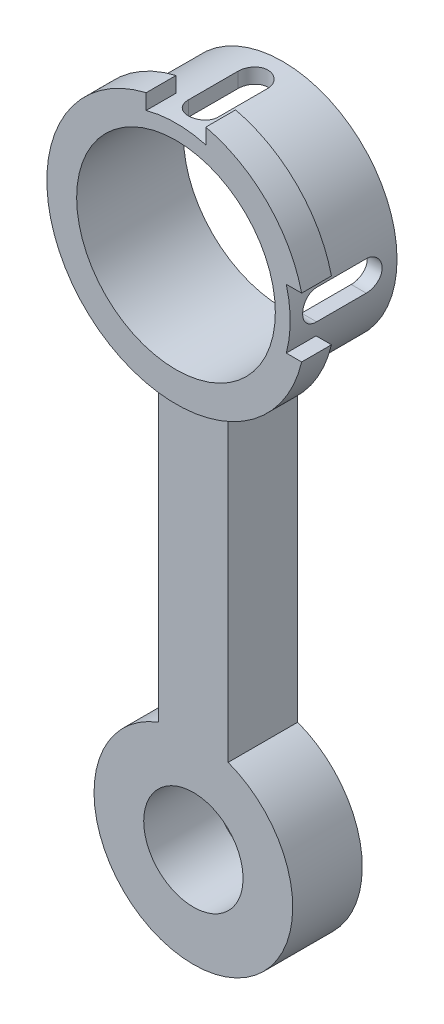
SolidWorks part; units mm, degrees
ref_plane "Alzado" through (0, 0, 0) normal (0, 0, 1) x (1, 0, 0)
ref_plane "Planta" through (0, 0, 0) normal (0, 1, 0) x (1, 0, 0)
ref_plane "Vista lateral" through (0, 0, 0) normal (1, 0, 0) x (0, 0, -1)
sketch "Croquis1" plane through (0, 0, 0) normal (0, 0, 1) x (1, 0, 0)
  circle A0 centre (0, 0) radius 10
  dimension "D1" = 20
extrude "Saliente-Extruir1" add sketch "Croquis1" along normal blind 3
sketch "Croquis2" plane through (0, 0, 3) normal (0, 0, 1) x (1, 0, 0)
  circle A0 centre (0, 0) radius 2.5
  circle A1 centre (0, 0) radius 4
  circle A2 centre (0, 0) radius 11.5
  circle A3 centre (0, 0) radius 10
  circle M1 centre (0, 0) radius 10
  dimension "D1" = 5
  dimension "D2" = 8
  dimension "D3" = 23
extrude "Saliente-Extruir3" add sketch "Croquis2" along normal blind 8 separate body contours A2 M1
sketch "Croquis3" plane through (0, 0, 3) normal (0, 0, -1) x (-1, 0, 0)
  circle A0 centre (0, 0) radius 11.5
  circle A1 centre (0, 0) radius 10
extrude "Saliente-Extruir4" add sketch "Croquis3" along normal up to surface (3 mm away) up to face at (10, 0, 0)
ref_plane "Plano1" through (0, 11.5, 0) normal (0, 1, 0) x (1, 0, 0)
sketch "Croquis4" plane through (0, 11.5, 0) normal (0, 1, 0) x (1, 0, 0)
  line L0 (0, -9.5) -> (0, -11) construction
  line L2 (0, -8) -> (0, -3) construction
  line L3 (-1.5, -8) -> (-1.5, -3)
  line L4 (1.5, -8) -> (1.5, -3)
  line L5 (-11.5, -11) -> (11.5, -11) construction
  line L6 (0, -1.5) -> (0, 0) construction
  arc A1 (-1.5, -8) -> (1.5, -8) centre (0, -8) ccw
  arc A2 (1.5, -3) -> (-1.5, -3) centre (0, -3) ccw
  point P0 (0, -5.5)
  dimension "D2" = 1.5
  dimension "D1" = 1.5
  dimension "D3" = 1.5
extrude "Cortar-Extruir1" cut sketch "Croquis4" against normal blind 8
sketch "Croquis7" plane through (0, 0, 11) normal (0, 0, 1) x (1, 0, 0)
  line L0 (0, 11.5) -> (0, 0) construction
  line L1 (6.05, 11.5) -> (-6.05, 11.5) construction
  line L2 (0, 0) -> (11.5, 0) construction
  circle A0 centre (0, 0) radius 11.5 construction
ref_plane "Plano2" through (0, 11.5, 0) normal (0, 1, 0) x (1, 0, 0)
ref_plane "Plano3" through (0, 11.5, 0) normal (0, 1, 0) x (1, 0, 0)
sketch "Croquis9" plane through (0, 0, 11) normal (0, 0, 1) x (1, 0, 0)
  line L0 (11.5, 0) -> (11.5, 3)
  line L1 (11.5, 3) -> (12.0602, 3)
  line L2 (12.0602, 3) -> (12.0602, -3)
  line L3 (11.5, 0) -> (11.5, -3)
  line L4 (12.0602, -3) -> (11.5, -3)
  dimension "D1" = 3
  dimension "D2" = 3
extrude "Saliente-Extruir5" add sketch "Croquis9" against normal blind 8 separate body
sketch "Croquis10" plane through (12.0602, 0, 0) normal (1, 0, 0) x (0, 0, -1)
  line L0 (-11, 3) -> (-11, 0) construction
  line L1 (-11, -3) -> (-11, 3) construction
  line L2 (-3, 0) -> (-8, 0) construction
  line L3 (-3, -3) -> (-3, 3) construction
  line L6 (-3, -1.5) -> (-8, -1.5)
  line L7 (-3, 1.5) -> (-8, 1.5)
  line L8 (-11, 0) -> (-9.5, 0) construction
  line L9 (0, 0) -> (-1.5, 0) construction
  arc A2 (-3, -1.5) -> (-3, 1.5) centre (-3, 0) ccw
  arc A3 (-8, 1.5) -> (-8, -1.5) centre (-8, 0) ccw
  point P7 (-8.5994, 0)
  point P8 (-5.5, 0)
  point P17 (-9.5, 0)
  dimension "D2" = 1.5
  dimension "D3" = 1.5
  dimension "D1" = 1.5
extrude "Cortar-Extruir2" cut sketch "Croquis10" against normal blind 8
sketch "Croquis11" plane through (0, 0, 11) normal (0, 0, 1) x (1, 0, 0)
  line L1 (11.5, 3) -> (12.0602, 3)
  line L2 (11.5, 3) -> (11.5, -3)
  line L3 (11.5, -3) -> (12.0602, -3)
  line L4 (12.0602, 3) -> (12.0602, -3)
extrude "Cortar-Extruir3" cut sketch "Croquis11" against normal blind 8
ref_plane "Plano4" through (-11.5, 0, 0) normal (-1, 0, 0) x (0, 0, 1)
sketch "Croquis12" plane through (0, 0, 3) normal (0, 0, 1) x (1, 0, 0)
  line L0 (0, 0) -> (0, -11.5) construction
  line L1 (0, -11.5) -> (-2.5, -11.5)
  line L2 (0, -11.5) -> (2.5, -11.5)
  line L3 (-2.5, -11.5) -> (-2.5, -10.878)
  line L4 (-2.5, -11.5) -> (2.5, -11.5)
  line L5 (-2.5, -11.5) -> (-2.5, -61.5)
  line L6 (-2.5, -61.5) -> (2.5, -61.5)
  line L7 (2.5, -11.5) -> (2.5, -61.5)
  line L8 (-2.5, -10.878) -> (0, -10.878)
  line L9 (0, -10.878) -> (0, -11.5)
  line L10 (0, -10.878) -> (2.5, -10.878)
  line L11 (2.5, -10.878) -> (2.5, -11.5)
  circle A0 centre (0, 0) radius 11.5 construction
  dimension "D1" = 2.5
  dimension "D2" = 2.5
  dimension "D3" = 50
extrude "Saliente-Extruir6" add sketch "Croquis12" against normal up to surface (3 mm away) contours L9 L8 L3 L1 | L11 L10 L9 L2 | L7 L2 L1 L5 L6 up to face at (11.5, 0, 0)
sketch "Croquis13" plane through (0, 0, 3) normal (0, 0, 1) x (1, 0, 0)
  line L1 (-2.5, -11.225) -> (2.5, -11.225)
  line L2 (-2.5, -11.225) -> (-2.5, -61.5)
  line L3 (-2.5, -61.5) -> (2.5, -61.5)
  line L4 (2.5, -11.225) -> (2.5, -61.5)
extrude "Saliente-Extruir7" add sketch "Croquis13" along normal up to surface (8 mm away) up to face at (10, 0, 11)
sketch "Croquis15" plane through (2.5, 0, 0) normal (1, 0, 0) x (0, 0, -1)
  line L0 (0, -11.225) -> (-11, -11.225) construction
  line L1 (-11, -61.5) -> (-9, -61.5)
  line L2 (-11, -61.5) -> (-11, -11.225)
  line L3 (-11, -11.225) -> (-9, -11.225)
  line L4 (-9, -61.5) -> (-9, -11.225)
  line L6 (0, -61.5) -> (-2, -61.5)
  line L7 (0, -61.5) -> (0, -11.225)
  line L8 (0, -11.225) -> (-2, -11.225)
  line L9 (-2, -61.5) -> (-2, -11.225)
  dimension "D1" = 2
  dimension "D2" = 2
extrude "Cortar-Extruir4" cut sketch "Croquis15" against normal blind 8
sketch "Croquis16" plane through (0, 0, 9) normal (0, 0, 1) x (1, 0, 0)
  line L0 (-2.5, -61.5) -> (-3.5, -61.5)
  line L1 (2.5, -61.5) -> (3.5, -61.5)
  line L2 (-3.5, -61.5) -> (-3.5, -10.233)
  line L3 (-3.5, -10.233) -> (3.5, -10.233)
  line L4 (3.5, -10.233) -> (3.5, -61.5)
  line L9 (-2.5, -61.5) -> (2.5, -61.5)
  line L10 (2.5, -61.5) -> (2.5, -11.225)
  line L11 (2.5, -11.225) -> (-2.5, -11.225)
  line L12 (-2.5, -11.225) -> (-2.5, -61.5)
  line L13 (-2.5, -61.5) -> (2.5, -61.5)
  dimension "D1" = 1
  dimension "D2" = 1
  dimension "D3" = 0
extrude "Saliente-Extruir8" add sketch "Croquis16" against normal up to surface (7 mm away) up to face at (0, -36.3625, 2)
sketch "Croquis21" plane through (0, 0, 2) normal (0, 0, -1) x (-1, 0, 0)
  line L0 (0, -11.225) -> (0, -52.725) construction
  line L1 (2.5, -11.225) -> (-2.5, -11.225) construction
  circle A0 centre (0, -52.725) radius 10
  dimension "D2" = 20
  dimension "D1" = 41.5
extrude "Saliente-Extruir9" add sketch "Croquis21" against normal up to surface (7 mm away) up to face at (0, -27.8969, 9)
sketch "Croquis22" plane through (0, 0, 2) normal (0, 0, -1) x (-1, 0, 0)
  circle A0 centre (0, -52.725) radius 5
  dimension "D1" = 10
extrude "Cortar-Extruir5" cut sketch "Croquis22" against normal blind 30
sketch "Croquis23" plane through (0, 0, 11) normal (0, 0, 1) x (1, 0, 0)
  line L0 (-2.5, -11.225) -> (2.5, -11.225) construction
  line L1 (-2.5, -11.225) -> (2.5, -11.225)
  arc A0 (2.5, -11.225) -> (-2.5, -11.225) centre (0, 0) ccw construction
  arc A1 (2.5, -11.225) -> (-2.5, -11.225) centre (0, 0) ccw
  circle A2 centre (0, 0) radius 10 construction
  circle A3 centre (0, 0) radius 10
extrude "Saliente-Extruir10" add sketch "Croquis23" along normal blind 1.25
sketch "Croquis24" plane through (0, 0, 12.25) normal (0, 0, 1) x (1, 0, 0)
  line L0 (-2.5, -11.225) -> (2.5, -11.225) construction
  line L1 (-2.5, -11.225) -> (2.5, -11.225)
  circle A0 centre (0, 0) radius 10 construction
  arc A1 (2.5, -11.225) -> (-2.5, -11.225) centre (0, 0) ccw construction
  circle A2 centre (0, 0) radius 10
  arc A3 (2.5, -11.225) -> (-2.5, -11.225) centre (0, 0) ccw
extrude "Cortar-Extruir6" cut sketch "Croquis24" against normal blind 1.5
sketch "Croquis25" plane through (0, 0, 10.75) normal (0, 0, 1) x (1, 0, 0)
  circle A0 centre (0, 0) radius 13
  arc A1 (2.5, -11.225) -> (-2.5, -11.225) centre (0, 0) ccw construction
  arc A2 (2.5, -11.225) -> (-2.5, -11.225) centre (0, 0) ccw
  arc M2 (2.5, -11.225) -> (-2.5, -11.225) centre (0, 0) ccw
  line M3 (-2.5, -11.225) -> (2.5, -11.225)
  dimension "D1" = 26
  dimension "D2" = 23
extrude "Saliente-Extruir11" add sketch "Croquis25" against normal blind 3 contours A0 M2 M3
sketch "Croquis27" plane through (0, 0, 0) normal (0, 0, -1) x (-1, 0, 0)
  line L1 (6.05, 11.5) -> (-6.05, 11.5) construction
  line L3 (3, 11.5) -> (3, 12.6491)
  line L7 (3, 12.6491) -> (3, 13.5864)
  line L8 (3, 13.5864) -> (-0.0015, 13.5864)
  line L10 (3, 11.5) -> (3, 11.3699)
  line L11 (-3, 11.5) -> (-3, 11.3699)
  line L12 (3, 11.5) -> (-3, 11.5)
  line L13 (-0.0015, 13.5864) -> (-3, 13.5864)
  line L14 (-3, 13.5864) -> (-3, 11.3699)
  line L15 (-3, 11.3699) -> (-3, 11.1018)
  line L16 (3, 11.3699) -> (3, 11.1018)
  arc A0 (3.5, -12.52) -> (-3.5, -12.52) centre (0, 0) ccw construction
  arc A2 (2.5, -11.225) -> (-2.5, -11.225) centre (0, 0) ccw construction
  arc A3 (2.5, -11.225) -> (-2.5, -11.225) centre (0, 0) ccw
  arc M6 (2.5, -11.225) -> (-2.5, -11.225) centre (0, 0) ccw
  dimension "D1" = 3.0015
  dimension "D2" = 3
  dimension "D3" = 3
extrude "Cortar-Extruir10" cut sketch "Croquis27" against normal blind 13 contours L11 L15 L12 M6 | L16 L10 L12 M6 | L13 L14 L12 L3 L7 L8
sketch "Croquis28" plane through (0, 0, 0) normal (0, 0, -1) x (-1, 0, 0)
  line L0 (-11.5, 0) -> (-11.5, 3)
  line L1 (-11.5, 0) -> (-11.5, -3)
  line L2 (-11.5, 3) -> (-11.1018, 3)
  line L3 (-11.5, -3) -> (-11.1018, -3)
  line L4 (-11.5, -3) -> (-13.8026, -3)
  line L5 (-13.8026, -3) -> (-13.8026, 3)
  line L6 (-13.8026, 3) -> (-11.5, 3)
  arc A0 (-11.4018, -1.5) -> (-3.5, -10.9545) centre (0, 0) ccw construction
  arc M3 (2.5, -11.225) -> (-2.5, -11.225) centre (0, 0) ccw
  dimension "D1" = 3
  dimension "D2" = 3
extrude "Cortar-Extruir11" cut sketch "Croquis28" against normal blind 13 contours L6 L5 L4 L1 L0 | L2 L0 M3 | L1 L3 M3
sketch "Croquis30" plane through (0, 0, 3) normal (0, 0, 1) x (1, 0, 0)
  circle A0 centre (0, 0) radius 10
extrude "Cortar-Extruir14" cut sketch "Croquis30" against normal blind 10
